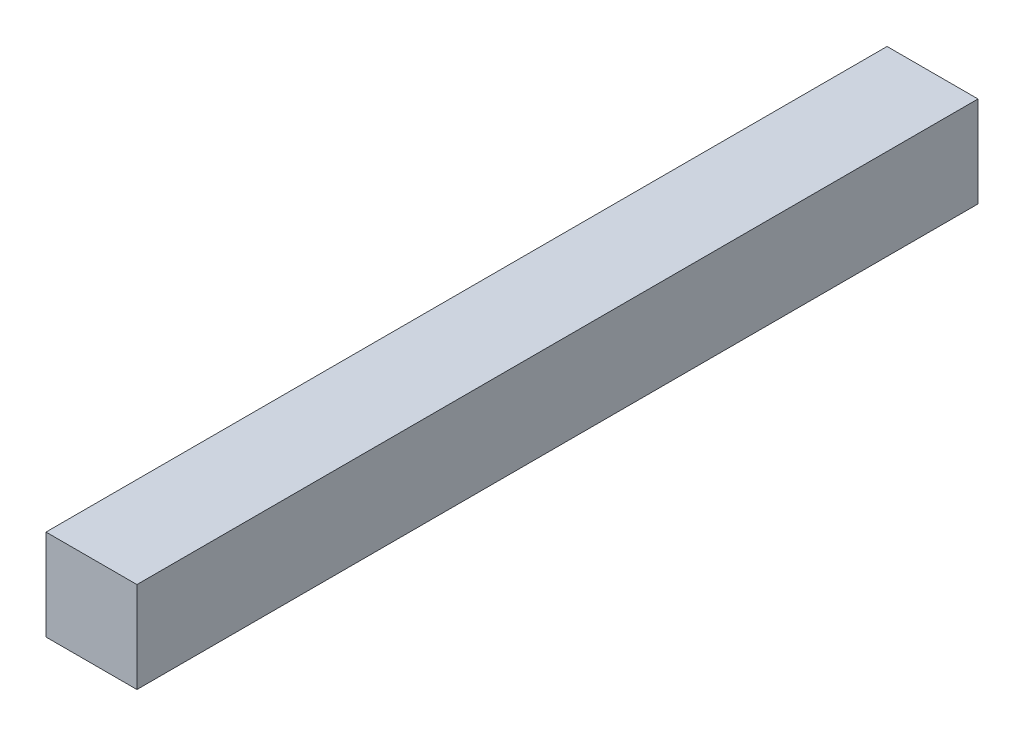
SolidWorks part; units mm, degrees
ref_plane "Front Plane" through (0, 0, 0) normal (0, 0, 1) x (1, 0, 0)
ref_plane "Top Plane" through (0, 0, 0) normal (0, 1, 0) x (1, 0, 0)
ref_plane "Right Plane" through (0, 0, 0) normal (1, 0, 0) x (0, 0, -1)
sketch "Sketch1" plane through (0, 0, 0) normal (1, 0, 0) x (0, 0, -1)
  line L0 (126.5431, 0) -> (-135.6999, 0) construction
  line L1 (0, 105.7009) -> (0, -97.8505) construction
  line L3 (-92.5, 10) -> (92.5, 10)
  line L4 (-92.5, 10) -> (-92.5, -10)
  line L5 (-92.5, -10) -> (92.5, -10)
  line L6 (92.5, 10) -> (92.5, -10)
  point P9 (92.5, 0)
  point P10 (0, 10)
  dimension "D1" = 20
  dimension "D2" = 185
extrude "Boss-Extrude1" add sketch "Sketch1" along normal blind 20
sketch "Sketch2" plane through (0, 0, 0) normal (1, 0, 0) x (0, 0, -1)
  line L0 (-92.5, 0) -> (92.5, 0) construction
  line L1 (0, 22.843) -> (0, -26.6092) construction
  line L2 (-92.5, 10) -> (-92.5, -10) construction
  line L3 (-92.5, 10) -> (-92.5, -10) construction
  line L4 (92.5, -10) -> (92.5, 10) construction
  line L5 (92.5, -10) -> (92.5, 10) construction
  text T0 "width" font "Century Gothic" height in points 20
extrude "Cut-Extrude1" cut sketch "Sketch2" along normal blind 4
